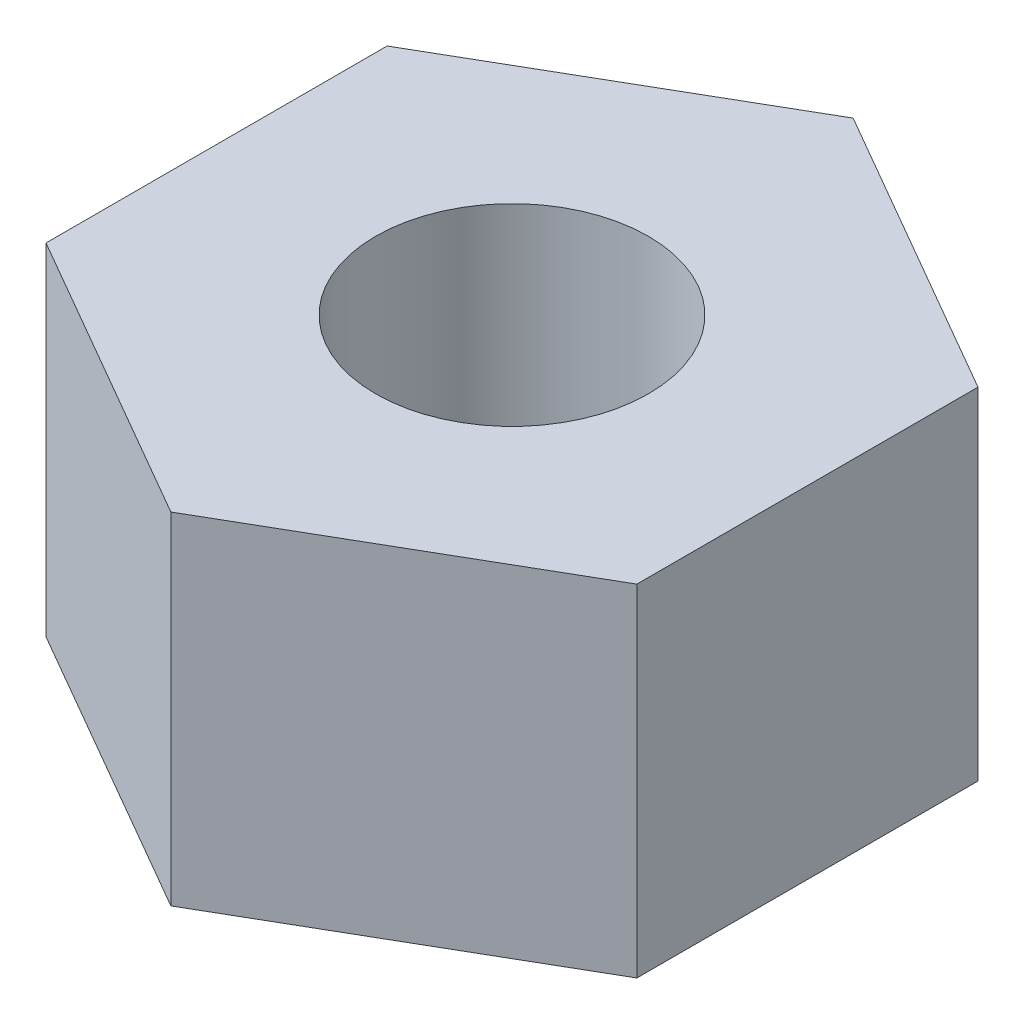
SolidWorks part; units mm, degrees
ref_plane "Front Plane" through (0, 0, 0) normal (0, 0, 1) x (1, 0, 0)
ref_plane "Top Plane" through (0, 0, 0) normal (0, 1, 0) x (1, 0, 0)
ref_plane "Right Plane" through (0, 0, 0) normal (1, 0, 0) x (0, 0, -1)
sketch "Sketch1" plane through (0, 0, 0) normal (0, 1, 0) x (1, 0, 0)
  line L1 (4.3301, -2.5) -> (4.3301, 2.5)
  line L2 (4.3301, 2.5) -> (0, 5)
  line L3 (0, 5) -> (-4.3301, 2.5)
  line L4 (-4.3301, 2.5) -> (-4.3301, -2.5)
  line L5 (-4.3301, -2.5) -> (0, -5)
  line L6 (0, -5) -> (4.3301, -2.5)
  circle A0 centre (0, 0) radius 4.3301 construction
  circle A1 centre (0, 0) radius 2
  dimension "D2" = 4
  dimension "D1" = 10
extrude "Boss-Extrude1" add sketch "Sketch1" along normal blind 5
